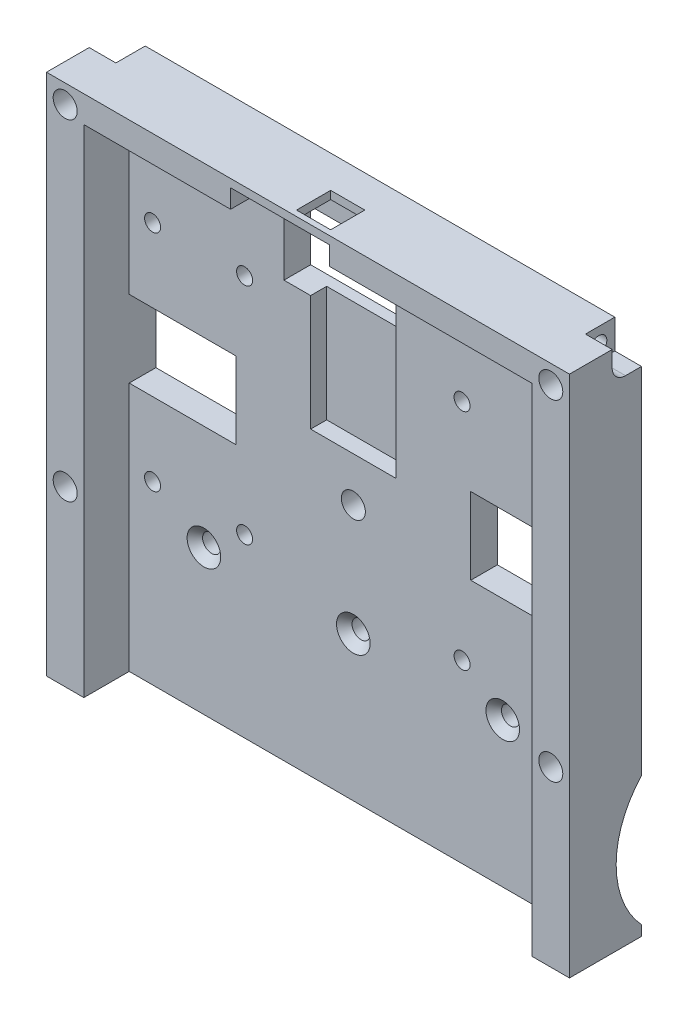
SolidWorks part; units mm, degrees
ref_plane "Front Plane" through (0, 0, 0) normal (0, 0, 1) x (1, 0, 0)
ref_plane "Top Plane" through (0, 0, 0) normal (0, 1, 0) x (1, 0, 0)
ref_plane "Right Plane" through (0, 0, 0) normal (1, 0, 0) x (0, 0, -1)
sketch "Sketch1" plane through (0, 0, 0) normal (0, 0, 1) x (1, 0, 0)
  line L1 (49, -40) -> (-49, -40)
  line L2 (49, -40) -> (49, 40)
  line L3 (49, 40) -> (-49, 40)
  line L4 (-49, -40) -> (-49, 40)
  line L5 (49, -40) -> (-49, 40) construction
  line L6 (49, 40) -> (-49, -40) construction
  point P0 (0, 0)
extrude "Boss-Extrude1" add sketch "Sketch1" along normal blind 5 contours L2 L1 L4 L3
sketch "Sketch2" plane through (0, 0, 5) normal (0, 0, 1) x (1, 0, 0)
  line L0 (49, -40) -> (-49, -40) construction
  line L1 (-49, 40) -> (-42, 40)
  line L2 (-49, 40) -> (-49, -40)
  line L3 (-49, -40) -> (-42, -40)
  line L4 (-42, 40) -> (-42, -40)
extrude "Boss-Extrude2" add sketch "Sketch2" along normal blind 8.5
sketch "Sketch3" plane through (0, 0, 5) normal (0, 0, 1) x (1, 0, 0)
  line L0 (49, -40) -> (49, 40) construction
  line L1 (49, 40) -> (42, 40)
  line L2 (49, 40) -> (49, -40)
  line L3 (49, -40) -> (42, -40)
  line L4 (42, 40) -> (42, -40)
  line L5 (49, 40) -> (-42, 40) construction
  line L6 (49, -40) -> (-42, -40) construction
extrude "Boss-Extrude3" add sketch "Sketch3" along normal blind 8.5
sketch "Sketch8" plane through (0, 40, 0) normal (0, 1, 0) x (1, 0, 0)
  line L1 (-42, -5) -> (42, -5)
  line L2 (-42, -5) -> (-42, -13.5)
  line L3 (-42, -13.5) -> (42, -13.5)
  line L4 (42, -5) -> (42, -13.5)
extrude "Boss-Extrude5" add sketch "Sketch8" against normal blind 5
sketch "Sketch13" plane through (0, 0, 5) normal (0, 0, 1) x (1, 0, 0)
  line L2 (42, -40) -> (-42, -40) construction
  line L4 (0, -40) -> (0, -10) construction
  circle A0 centre (0, -10) radius 2.25
  circle A1 centre (0, -10) radius 3.5
extrude "Cut-Extrude7" cut sketch "Sketch13" against normal blind 3.2 contours A0
sketch "Sketch14" plane through (0, 0, 5) normal (0, 0, 1) x (1, 0, 0)
  line L0 (0, -7.75) -> (0, 6.3272)
  line L1 (-8, 14.3272) -> (8, 14.3272)
  line L2 (-8, 14.3272) -> (-8, -1.6728)
  line L3 (8, 14.3272) -> (8, -1.6728)
  line L4 (-8, -1.6728) -> (8, -1.6728)
  line L5 (-8, 14.3272) -> (8, -1.6728) construction
  line L6 (8, 14.3272) -> (-8, -1.6728) construction
  circle A0 centre (0, -10) radius 2.25 construction
  circle A1 centre (0, -10) radius 2.25 construction
  dimension "D1" = 16
  dimension "D2" = 16
sketch "Sketch15" plane through (0, 0, 5) normal (0, 0, 1) x (1, 0, 0)
  line L0 (42, 35) -> (29, 35) construction
  line L1 (-29, 35) -> (-29, 17) construction
  line L2 (42, 35) -> (-42, 35) construction
  line L3 (-29, 17) -> (-37.62, 17) construction
  line L4 (-37.62, 17) -> (-20.38, 17) construction
  line L5 (-20.38, 17) -> (-29, 17) construction
  line L6 (-29, 17) -> (-29, -25) construction
  line L7 (-29, -25) -> (-37.62, -25) construction
  line L8 (-42, 35) -> (-29, 35) construction
  line L9 (-37.62, -25) -> (-20.38, -25) construction
  line L10 (29, 35) -> (29, 17) construction
  line L11 (29, 17) -> (20.38, 17) construction
  line L12 (20.38, 17) -> (37.62, 17) construction
  line L13 (37.62, 17) -> (29, 17) construction
  line L14 (29, 17) -> (29, -25) construction
  line L15 (29, -25) -> (20.38, -25) construction
  line L16 (20.38, -25) -> (37.62, -25) construction
  line L17 (-29, -40) -> (-29, -25) construction
  line L18 (42, -40) -> (-42, -40) construction
  line L20 (29, -25) -> (29, -40) construction
  circle A2 centre (-37.62, 17) radius 1.5
  circle A3 centre (-20.38, 17) radius 1.5
  circle A4 centre (-37.62, -25) radius 1.5
  circle A5 centre (-20.38, -25) radius 1.5
  circle A6 centre (20.38, -25) radius 1.5
  circle A7 centre (37.62, -25) radius 1.5
  circle A8 centre (37.62, 17) radius 1.5
  circle A9 centre (20.38, 17) radius 1.5
  circle A10 centre (-37.62, 17) radius 2.25
  circle A11 centre (-20.38, 17) radius 2.25
  circle A12 centre (-20.38, -25) radius 2.25
  circle A13 centre (-37.62, -25) radius 2.25
  circle A14 centre (37.62, 17) radius 2.25
  circle A15 centre (20.38, 17) radius 2.25
  circle A16 centre (37.62, -25) radius 2.25
  circle A17 centre (20.38, -25) radius 2.25
extrude "Cut-Extrude9" cut sketch "Sketch15" against normal blind 3.2 contours A2 | A3 | A5 | A4 | A6 | A7 | A8 | A9
extrude "Cut-Extrude13" cut sketch "Sketch14" against normal blind 3
sketch "Sketch18" plane through (0, 0, 5) normal (0, 0, 1) x (1, 0, 0)
  line L0 (0, 35) -> (0, 26) construction
  line L1 (-42, 35) -> (42, 35) construction
  line L2 (0, 35) -> (0, 29) construction
  line L3 (-8, 32) -> (8, 32)
  line L4 (-8, 32) -> (-8, 20)
  line L5 (-8, 20) -> (8, 20)
  line L6 (8, 32) -> (8, 20)
  line L7 (-8, 32) -> (8, 20) construction
  line L8 (-8, 20) -> (8, 32) construction
extrude "Cut-Extrude14" cut sketch "Sketch18" against normal through all
sketch "Sketch19" plane through (0, 0, 5) normal (0, 0, 1) x (1, 0, 0)
  line L1 (-8, 14.3272) -> (8, 14.3272)
  line L2 (-8, 14.3272) -> (-8, 20)
  line L3 (-8, 20) -> (8, 20)
  line L4 (8, 14.3272) -> (8, 20)
extrude "Cut-Extrude15" cut sketch "Sketch19" against normal blind 3
sketch "Sketch20" plane through (0, 0, 0) normal (0, 0, -1) x (-1, 0, 0)
  line L0 (0, -40) -> (0, 10) construction
  line L1 (-49, -40) -> (49, -40) construction
  line L2 (0, 10) -> (0, 21.5) construction
  line L3 (0, 21.5) -> (0, -15) construction
  line L4 (0, 21.5) -> (18.25, 21.5) construction
  line L5 (0, 21.5) -> (-18.25, 21.5) construction
  line L6 (0, -15) -> (18.25, -15) construction
  line L7 (18.25, -15) -> (-18.25, -15) construction
  line L8 (0, 10) -> (0, 21.5) construction
  line L9 (0, 10) -> (0, -15) construction
  line L10 (0, -40) -> (0, -15) construction
  line L11 (0, -15) -> (0, 21.5) construction
  line L12 (0, -40) -> (0, -15) construction
  line L13 (0, 21.5) -> (0, 17.5) construction
  line L14 (18.25, 21.5) -> (18.25, -15) construction
  line L15 (18.25, -15) -> (-18.25, -15) construction
  line L16 (-18.25, -15) -> (-18.25, 21.5) construction
  line L17 (-18.25, 21.5) -> (18.25, 21.5) construction
  line L18 (0, -40) -> (0, -13.75) construction
  circle A0 centre (18.25, 21.5) radius 2.25
  circle A1 centre (-18.25, 21.5) radius 2.25
  circle A2 centre (18.25, -15) radius 2.25
  circle A3 centre (-18.25, -15) radius 2.25
  circle A4 centre (-18.25, 21.5) radius 3.25
  circle A5 centre (18.25, 21.5) radius 3.25
  circle A6 centre (18.25, -15) radius 3.25
  circle A7 centre (-18.25, -15) radius 3.25
extrude "Cut-Extrude20" cut sketch "Sketch20" against normal blind 3.2 contours A1 | A0 | A2 | A3
sketch "Sketch26" plane through (0, -40, 0) normal (0, -1, 0) x (-1, 0, 0)
  line L0 (49, -13.5) -> (42, -13.5)
  line L1 (42, -13.5) -> (42, -5)
  line L2 (42, -5) -> (-42, -5)
  line L3 (-42, -5) -> (-42, -13.5)
  line L4 (-42, -13.5) -> (-49, -13.5)
  line L5 (-49, -13.5) -> (-49, 0)
  line L6 (-49, 0) -> (49, 0)
  line L7 (49, 0) -> (49, -13.5)
extrude "Boss-Extrude7" add sketch "Sketch26" along normal blind 10
sketch "Sketch42" plane through (0, 0, 13.5) normal (0, 0, 1) x (1, 0, 0)
  line L0 (-49, 40) -> (-49, 36.5) construction
  line L1 (-49, 40) -> (-49, -50) construction
  line L2 (-49, 36.5) -> (-45.5, 36.5) construction
  line L3 (-45.5, 36.5) -> (45.5, 36.5) construction
  line L4 (-45.5, 36.5) -> (-45.5, -11.5) construction
  line L5 (45.5, 36.5) -> (45.5, -11.5) construction
  circle A0 centre (-45.5, 36.5) radius 2.25
  circle A1 centre (45.5, 36.5) radius 2.25
sketch "Sketch47" plane through (0, -50, 0) normal (0, -1, 0) x (-1, 0, 0)
  line L0 (49, -13.5) -> (42, -13.5)
  line L1 (42, -13.5) -> (42, -5)
  line L2 (42, -5) -> (-42, -5)
  line L3 (-42, -5) -> (-42, -13.5)
  line L4 (-42, -13.5) -> (-49, -13.5)
  line L5 (-49, -13.5) -> (-49, 0)
  line L6 (-49, 0) -> (49, 0)
  line L7 (49, 0) -> (49, -13.5)
extrude "Boss-Extrude9" add sketch "Sketch47" along normal blind 8
sketch "Sketch48" plane through (0, 0, 5) normal (0, 0, 1) x (1, 0, 0)
  line L0 (0, -58) -> (0, -30.88) construction
  line L1 (42, -58) -> (-42, -58) construction
  line L2 (0, -30.88) -> (28, -30.88) construction
  line L3 (0, -30.88) -> (-28, -30.88) construction
hole_wizard "CSK for M3 Flat Head Machine Screw1" positions "Sketch49" profile "Sketch50" countersink size "M3" standard "ANSI Metric" end condition through all
sketch "Sketch49" plane through (0, 0, 5) normal (0, 0, 1) x (1, 0, 0)
  point P0 (28, -30.88)
  point P3 (0, -30.88)
  point P6 (-28, -30.88)
sketch "Sketch50" plane through (28, -30.88, 5) normal (1, 0, 0) x (0, -1, 0)
  line L0 (0, 0) -> (0, 5)
  line L1 (0, 5) -> (1.7, 5)
  line L2 (1.7, 5) -> (1.7, 1.45)
  line L3 (1.7, 1.45) -> (3.15, 0)
  line L5 (3.15, 0) -> (0, 0)
  line L6 (-1.7, 1.45) -> (-3.15, 0) construction
  line L11 (0, -6.35) -> (0, 107.95) construction
  dimension "Thru Hole Dia." = 3.4
  dimension "Thru Hole Depth" = 5
  dimension "Near C'Sink Dia." = 6.3
  dimension "Near C'Sink Angle" = 90
sketch "Sketch51" plane through (-49, 0, 0) normal (-1, 0, 0) x (0, 0, 1)
  line L0 (0, -58) -> (0, -44) construction
  line L1 (0, -58) -> (0, 40) construction
  line L2 (0, -44) -> (-13, -44) construction
  circle A0 centre (-13, -44) radius 17.75
extrude "Cut-Extrude23" cut sketch "Sketch51" against normal blind 8
sketch "Sketch52" plane through (49, 0, 0) normal (1, 0, 0) x (0, 0, -1)
  line L0 (0, -58) -> (0, -44) construction
  line L1 (0, -58) -> (0, 40) construction
  line L2 (0, -44) -> (13, -44) construction
  circle A0 centre (13, -44) radius 17.75
extrude "Cut-Extrude24" cut sketch "Sketch52" against normal blind 8
extrude "Cut-Extrude25" cut sketch "Sketch42" against normal blind 4.25
sketch "Sketch53" plane through (0, 0, 13.5) normal (0, 0, 1) x (1, 0, 0)
  line L0 (-45.5, 36.5) -> (-45.5, -25.5) construction
  line L1 (-45.5, -25.5) -> (45.5, -25.5) construction
  circle A0 centre (-45.5, -25.5) radius 2.25
  circle A1 centre (45.5, -25.5) radius 2.25
extrude "Cut-Extrude26" cut sketch "Sketch53" against normal blind 8.25
sketch "Sketch54" plane through (-49, 0, 0) normal (-1, 0, 0) x (0, 0, 1)
  line L0 (0, 40) -> (3, 40) construction
  line L1 (13.5, 40) -> (0, 40) construction
  line L2 (3, 40) -> (3, 37) construction
  circle A0 centre (3, 37) radius 1.5
extrude "Cut-Extrude27" cut sketch "Sketch54" against normal blind 13.25
sketch "Sketch55" plane through (-49, 0, 0) normal (-1, 0, 0) x (0, 0, 1)
  line L0 (5.5, 37) -> (5.5, 40)
  line L5 (13.5, 40) -> (0, 40) construction
  line L8 (3, 37) -> (3, 34.5) construction
  line L9 (5.5, 40) -> (0, 40)
  line L10 (0, 40) -> (0, 34.5)
  line L11 (0, -31.9144) -> (0, 40) construction
  line L12 (0, 34.5) -> (3, 34.5)
  arc A1 (3, 34.5) -> (5.5, 37) centre (3, 37) ccw
extrude "Cut-Extrude28" cut sketch "Sketch55" against normal blind 5
sketch "Sketch56" plane through (49, 0, 0) normal (1, 0, 0) x (0, 0, -1)
  line L0 (0, 40) -> (-3, 40) construction
  line L1 (-13.5, 40) -> (0, 40) construction
  line L2 (-3, 40) -> (-3, 37) construction
  circle A0 centre (-3, 37) radius 1.5
extrude "Cut-Extrude29" cut sketch "Sketch56" against normal blind 13.25
sketch "Sketch57" plane through (49, 0, 0) normal (1, 0, 0) x (0, 0, -1)
  line L0 (-5.5, 37) -> (-5.5, 40)
  line L2 (-13.5, 40) -> (-5.5, 40) construction
  line L4 (-5.5, 40) -> (0, 40)
  line L6 (0, 40) -> (0, 34.5)
  line L7 (-3, 37) -> (-3, 34.5) construction
  line L8 (0, -31.9144) -> (0, 34.5) construction
  line L9 (0, 34.5) -> (-3, 34.5)
  arc A2 (-3, 34.5) -> (-5.5, 37) centre (-3, 37) cw
extrude "Cut-Extrude30" cut sketch "Sketch57" against normal blind 5
sketch "Sketch65" plane through (0, 0, 5) normal (0, 0, 1) x (1, 0, 0)
  line L0 (-42, 35) -> (-29, 35) construction
  line L1 (-42, 35) -> (42, 35) construction
  line L2 (-29, 35) -> (-29, -4) construction
  line L3 (42, 35) -> (28.8, 35) construction
  line L4 (28.8, 35) -> (28.8, -4) construction
  line L5 (-29, -4) -> (-29, 3.2) construction
  line L10 (-29, 3.2) -> (-42, 3.2) construction
  line L11 (28.8, -4) -> (28.8, 3.2) construction
  line L17 (42, 3.2) -> (22, 3.2)
  line L18 (-42, 3.2) -> (-22, 3.2)
  line L19 (-42, 3.2) -> (-42, -11.2)
  line L20 (-42, -11.2) -> (-22, -11.2)
  line L21 (-22, 3.2) -> (-22, -11.2)
  line L22 (42, 3.2) -> (42, -11.2)
  line L23 (42, -11.2) -> (22, -11.2)
  line L24 (22, 3.2) -> (22, -11.2)
extrude "Cut-Extrude31" cut sketch "Sketch65" against normal through all
sketch "Sketch69" plane through (0, 35, 0) normal (0, -1, 0) x (1, 0, 0)
  line L0 (0, 13.5) -> (0, 9.25) construction
  line L1 (0, 9.25) -> (0, 12.45) construction
  line L2 (0, 12.45) -> (3.2, 12.45)
  line L3 (3.2, 12.45) -> (3.2, 6.05)
  line L8 (3.2, 6.05) -> (-3.2, 6.05)
  line L9 (-3.2, 6.05) -> (-3.2, 12.45)
  line L10 (-3.2, 12.45) -> (0, 12.45)
extrude "Cut-Extrude33" cut sketch "Sketch69" against normal blind 13.5
sketch "Sketch75" plane through (0, 0, 13.5) normal (0, 0, 1) x (1, 0, 0)
  line L0 (0, 40) -> (0, 38.5) construction
  line L1 (0, 38.5) -> (9.3, 38.5) construction
  line L2 (9.3, 38.5) -> (-19.2, 38.5) construction
  line L5 (-19.2, 31.5) -> (9.3, 31.5)
  line L7 (-19.2, 31.5) -> (-19.2, 38.5)
  line L8 (-19.2, 38.5) -> (9.3, 38.5)
  line L9 (9.3, 38.5) -> (9.3, 31.5)
extrude "Cut-Extrude39" cut sketch "Sketch75" against normal blind 11
sketch "Sketch80" plane through (0, 0, 5) normal (0, 0, 1) x (1, 0, 0)
  line L1 (-8, 32) -> (-13, 32)
  line L2 (-8, 32) -> (-8, 20)
  line L3 (-8, 20) -> (-13, 20)
  line L4 (-13, 32) -> (-13, 20)
extrude "Cut-Extrude42" cut sketch "Sketch80" against normal through all
sketch "Sketch82" plane through (0, 0, 13.5) normal (0, 0, 1) x (1, 0, 0)
  line L0 (0, 40) -> (9.5, 40) construction
  line L1 (9.5, 40) -> (9.5, 38.5) construction
  line L2 (0, 40) -> (-20, 40) construction
  line L3 (-20, 40) -> (-20, 38.5) construction
  line L5 (-20, 38.5) -> (-19.2, 38.5)
  line L6 (-20, 38.5) -> (-20, 31.5)
  line L7 (-20, 31.5) -> (-19.2, 31.5)
  line L8 (-19.2, 38.5) -> (-19.2, 31.5)
  line L9 (9.5, 38.5) -> (9.3, 38.5)
  line L10 (9.5, 38.5) -> (9.5, 31.5)
  line L11 (9.5, 31.5) -> (9.3, 31.5)
  line L12 (9.3, 38.5) -> (9.3, 31.5)
extrude "Cut-Extrude43" cut sketch "Sketch82" against normal blind 11
sketch "Sketch84" plane through (0, 38.5, 0) normal (0, -1, 0) x (1, 0, 0)
  line L0 (4, 13.5) -> (6.7365, 10.55) construction
  line L1 (6.7365, 10.55) -> (6.7365, 9.05) construction
  line L2 (9.5, 9.05) -> (6.5, 9.05) construction
  line L3 (-20, 9.05) -> (-17, 9.05) construction
  line L5 (-20, 5) -> (-14.5, 5)
  line L6 (-20, 5) -> (-20, 13.5)
  line L7 (-20, 13.5) -> (-14.5, 13.5)
  line L8 (-14.5, 5) -> (-14.5, 13.5)
  line L9 (9.5, 13.5) -> (4, 13.5)
  line L10 (9.5, 13.5) -> (9.5, 5)
  line L11 (9.5, 5) -> (4, 5)
  line L12 (4, 13.5) -> (4, 5)
  circle A0 centre (6.5, 9.05) radius 1.5
  circle A1 centre (-17, 9.05) radius 1.5
extrude "Boss-Extrude10" add sketch "Sketch84" along normal blind 3.5 contours L6 L5 L8 L7 | L10 L9 L12 L11 | A1 | A0
sketch "Sketch86" plane through (0, 0, 2.5) normal (0, 0, 1) x (1, 0, 0)
  line L1 (-20, 38.5) -> (-14.5, 38.5)
  line L2 (-20, 38.5) -> (-20, 35)
  line L3 (-20, 35) -> (-14.5, 35)
  line L4 (-14.5, 38.5) -> (-14.5, 35)
  line L5 (9.5, 38.5) -> (4, 38.5)
  line L6 (9.5, 38.5) -> (9.5, 35)
  line L7 (9.5, 35) -> (4, 35)
  line L8 (4, 38.5) -> (4, 35)
extrude "Boss-Extrude11" add sketch "Sketch86" along normal blind 3.5
